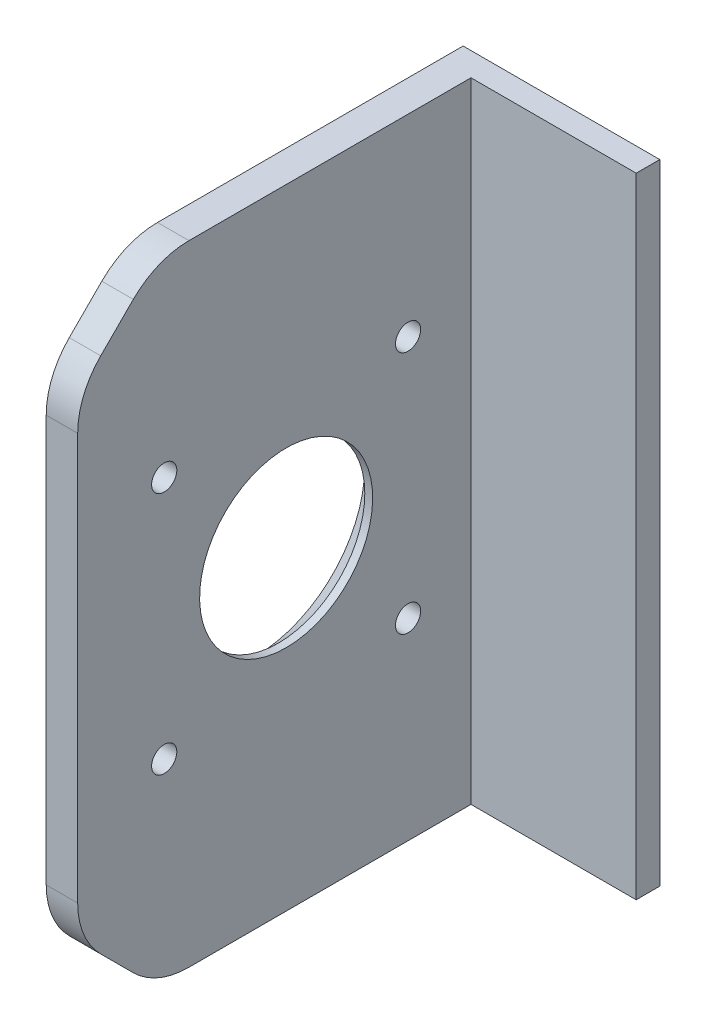
SolidWorks part; units mm, degrees
material "ABS"
ref_plane "Alzado" through (0, 0, 0) normal (0, 0, 1) x (1, 0, 0)
ref_plane "Planta" through (0, 0, 0) normal (0, 1, 0) x (1, 0, 0)
ref_plane "Vista lateral" through (0, 0, 0) normal (1, 0, 0) x (0, 0, -1)
sketch "Croquis1" plane through (0, 0, 0) normal (0, 0, 1) x (1, 0, 0)
  line L1 (-12.5, 40) -> (12.5, 40)
  line L2 (-12.5, 40) -> (-12.5, -40)
  line L3 (-12.5, -40) -> (12.5, -40)
  line L4 (12.5, 40) -> (12.5, -40)
  point P4 (-12.5, 0)
  point P6 (0, -40)
  dimension "D1" = 25
  dimension "D2" = 80
extrude "Saliente-Extruir1" add sketch "Croquis1" along normal blind 3
sketch "Croquis2" plane through (0, 0, 3) normal (0, 0, 1) x (1, 0, 0)
  line L0 (-12.5, -40) -> (12.5, -40) construction
  line L1 (-12.5, 40) -> (-8.5, 40)
  line L2 (-12.5, 40) -> (-12.5, -40)
  line L3 (-12.5, -40) -> (-8.5, -40)
  line L4 (-8.5, 40) -> (-8.5, -40)
  dimension "D1" = 4
extrude "Saliente-Extruir2" add sketch "Croquis2" along normal blind 50
chamfer "Chaflán1" distance 10 angle 45 2 edges at (-10.5, -40, 53) (-10.5, 40, 53)
fillet "Redondeo1" radius 10 4 edges at (-10.5, -40, 43) (-10.5, -30, 53) (-10.5, 30, 53) (-10.5, 40, 43)
sketch "Croquis3" plane through (-12.5, 0, 0) normal (-1, 0, 0) x (0, 0, 1)
  line L0 (0, 0) -> (53, 0) construction
  line L1 (0, 40) -> (0, -40) construction
  line L2 (53, 25.8579) -> (53, -25.8579) construction
  circle A0 centre (11, 15.5) radius 1.6
  circle A1 centre (42, 15.5) radius 1.6
  circle A2 centre (11, -15.5) radius 1.6
  circle A3 centre (42, -15.5) radius 1.6
  circle A4 centre (26.5, 0) radius 11
  point P17 (0, 0)
  point P18 (0, 0)
  point P19 (0, 0)
  point P20 (0, 0)
  dimension "D1" = 22
  dimension "D7" = 3.2
  dimension "D2" = 26.5
  dimension "D3" = 31
  dimension "D4" = 31
  dimension "D5" = 15.5
  dimension "D6" = 15.5
extrude "Cortar-Extruir1" cut sketch "Croquis3" against normal blind 50
chamfer "Chaflán2" distance 3 angle 45 1 edges at (-12.5, 0, 37.5)
